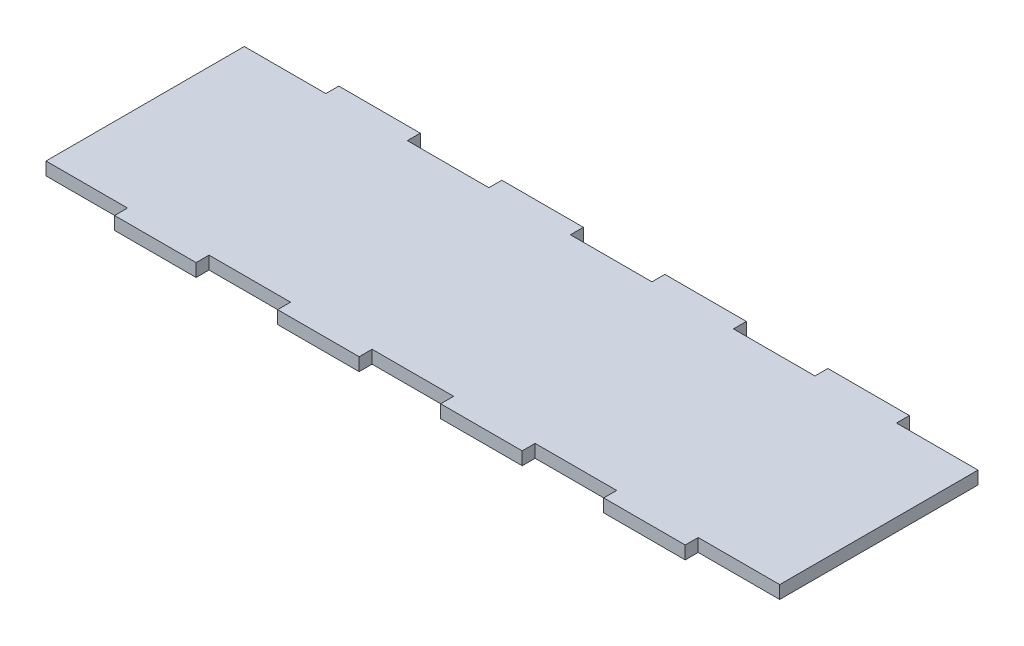
SolidWorks part; units mm, degrees
ref_plane "Front Plane" through (0, 0, 0) normal (0, 0, 1) x (1, 0, 0)
ref_plane "Top Plane" through (0, 0, 0) normal (0, 1, 0) x (1, 0, 0)
ref_plane "Right Plane" through (0, 0, 0) normal (1, 0, 0) x (0, 0, -1)
sketch "Sketch1" plane through (0, 0, 0) normal (0, 1, 0) x (1, 0, 0)
  line L0 (0, 0) -> (20, 0)
  line L1 (20, 0) -> (20, 3.175)
  line L2 (20, 3.175) -> (40, 3.175)
  line L3 (40, 3.175) -> (40, 0)
  line L4 (40, 0) -> (60, 0)
  line L5 (60, 0) -> (60, 3.175)
  line L6 (60, 3.175) -> (80, 3.175)
  line L7 (80, 3.175) -> (80, 0)
  line L8 (80, 0) -> (100, 0)
  line L9 (100, 0) -> (100, 3.175)
  line L10 (100, 3.175) -> (120, 3.175)
  line L11 (120, 3.175) -> (120, 0)
  line L12 (120, 0) -> (140, 0)
  line L13 (140, 0) -> (140, 3.175)
  line L14 (140, 3.175) -> (160, 3.175)
  line L15 (160, 3.175) -> (160, 0)
  line L16 (160, 0) -> (180, 0)
  line L17 (180, 0) -> (180, -48.65)
  line L18 (180, -24.325) -> (0, -24.325) construction
  line L19 (0, -48.65) -> (0, 0)
  line L20 (160, -48.65) -> (180, -48.65)
  line L21 (160, -51.825) -> (160, -48.65)
  line L22 (140, -51.825) -> (160, -51.825)
  line L23 (140, -48.65) -> (140, -51.825)
  line L24 (120, -48.65) -> (140, -48.65)
  line L25 (120, -51.825) -> (120, -48.65)
  line L26 (100, -51.825) -> (120, -51.825)
  line L27 (100, -48.65) -> (100, -51.825)
  line L28 (80, -48.65) -> (100, -48.65)
  line L29 (80, -51.825) -> (80, -48.65)
  line L30 (60, -51.825) -> (80, -51.825)
  line L31 (60, -48.65) -> (60, -51.825)
  line L32 (40, -48.65) -> (60, -48.65)
  line L33 (40, -51.825) -> (40, -48.65)
  line L34 (20, -51.825) -> (40, -51.825)
  line L35 (20, -48.65) -> (20, -51.825)
  line L36 (0, -48.65) -> (20, -48.65)
  dimension "D1" = 180
  dimension "D2" = 20
  dimension "D3" = 20
  dimension "D4" = 3.175
  dimension "D5" = 24.325
extrude "Boss-Extrude1" add sketch "Sketch1" along normal blind 3.175
